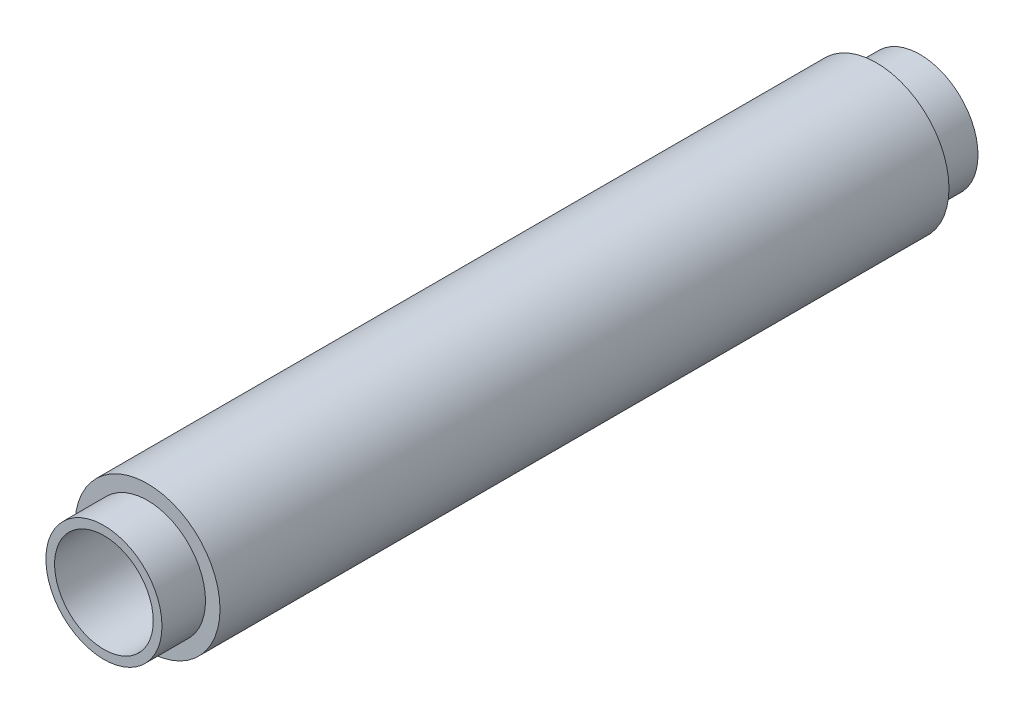
SolidWorks part; units mm, degrees
material "СТ3КП"
ref_plane "Спереди" through (0, 0, 0) normal (0, 0, 1) x (1, 0, 0)
ref_plane "Сверху" through (0, 0, 0) normal (0, 1, 0) x (1, 0, 0)
ref_plane "Справа" through (0, 0, 0) normal (1, 0, 0) x (0, 0, -1)
sketch "Эскиз1" plane through (0, 0, 0) normal (0, 1, 0) x (1, 0, 0)
  line L0 (-1000, 0) -> (49000, 0) construction
  line L1 (0, -1000) -> (0, 49000) construction
  line L3 (-25, 0) -> (-17, 0)
  line L4 (-25, 0) -> (-25, -125.6)
  line L5 (-20, -140.6) -> (-17, -140.6)
  line L6 (-17, 0) -> (-17, -140.6)
  line L7 (-21.5, -140.6) -> (21.5, -140.6) construction
  line L8 (21.5, -125.6) -> (-21.5, -125.6) construction
  line L9 (-20, -125.6) -> (-25, -125.6)
  line L10 (-20, -125.6) -> (-20, -140.6)
  line L13 (-20, -127.1) -> (-20, -139.1) construction
  dimension "D1" = 34
  dimension "D2" = 50
revolve "Повернуть1" add sketch "Эскиз1" angle 360 about L1
mirror "Зеркальное отражение1" about plane through (-25, 0, 0) normal (0, 0, 1) of "Повернуть1"
